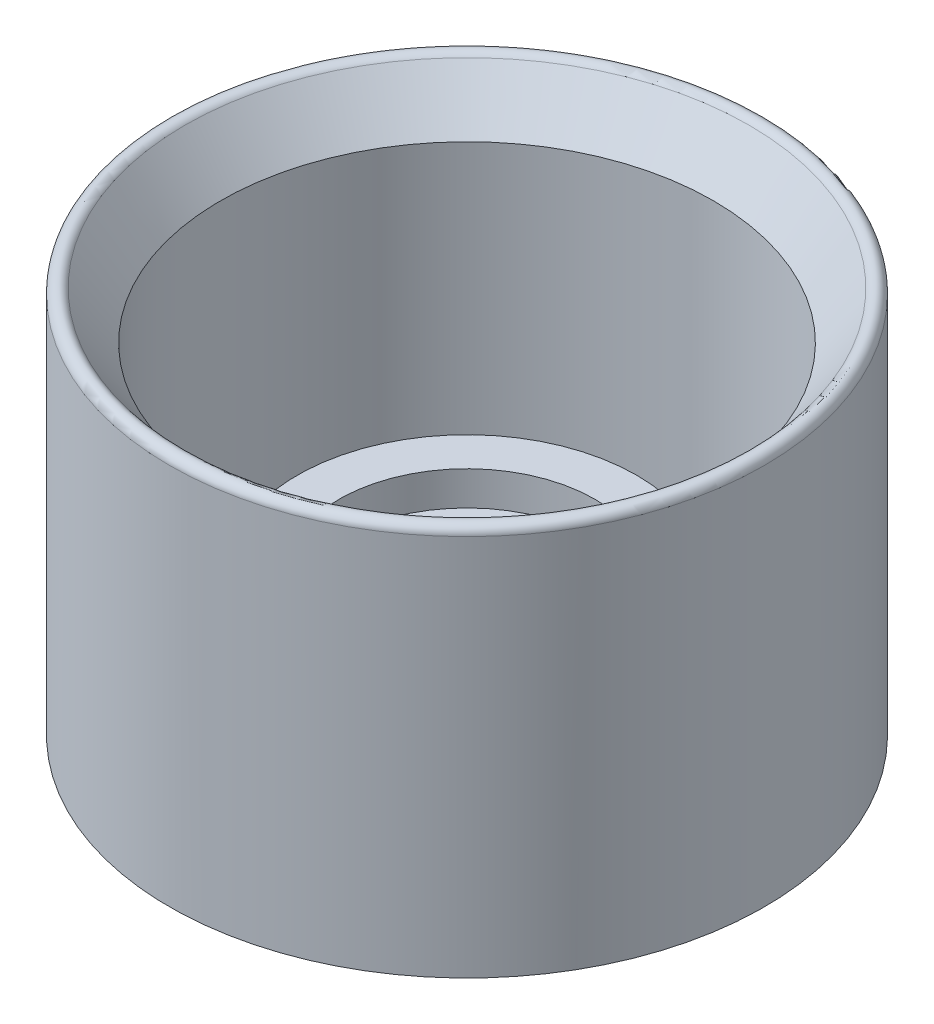
SolidWorks part; units mm, degrees
ref_plane "Спереди" through (0, 0, 0) normal (0, 0, 1) x (1, 0, 0)
ref_plane "Сверху" through (0, 0, 0) normal (0, 1, 0) x (1, 0, 0)
ref_plane "Справа" through (0, 0, 0) normal (1, 0, 0) x (0, 0, -1)
sketch "Эскиз1" plane through (0, 0, 0) normal (1, 0, 0) x (0, 0, -1)
  line L0 (0, 0) -> (0, 32527.5687) construction
  line L1 (1.5, 0) -> (17.5, 0)
  line L2 (17.5, 0) -> (17.5, 24)
  line L3 (17.5, 24) -> (14.5, 20)
  line L4 (14.5, 20) -> (14.5, 1.5)
  line L5 (14.5, 1.5) -> (11.5, 1.5)
  line L6 (11.5, 1.5) -> (11.5, 3.25)
  line L7 (11.5, 3.25) -> (10, 3.25)
  line L8 (10, 3.25) -> (10, 8.25)
  line L9 (10, 8.25) -> (7.55, 8.25)
  line L10 (7.55, 8.25) -> (7.55, 6.25)
  line L11 (7.55, 6.25) -> (1.5, 6.25)
  line L12 (1.5, 6.25) -> (1.5, 0)
  point P12 (7.8896, 6.9394)
  dimension "D1" = 3
  dimension "D2" = 3
  dimension "D3" = 1.5
  dimension "D4" = 29
  dimension "D5" = 4
  dimension "D6" = 18.5
  dimension "D7" = 1.75
  dimension "D8" = 23
  dimension "D9" = 20
  dimension "D10" = 6.75
  dimension "D11" = 2
  dimension "D12" = 15.1
revolve "Повернуть1" add sketch "Эскиз1" angle 360 about L0
fillet "Скругление1" radius 0.5 1 edges at (0, 24, -17.5)
